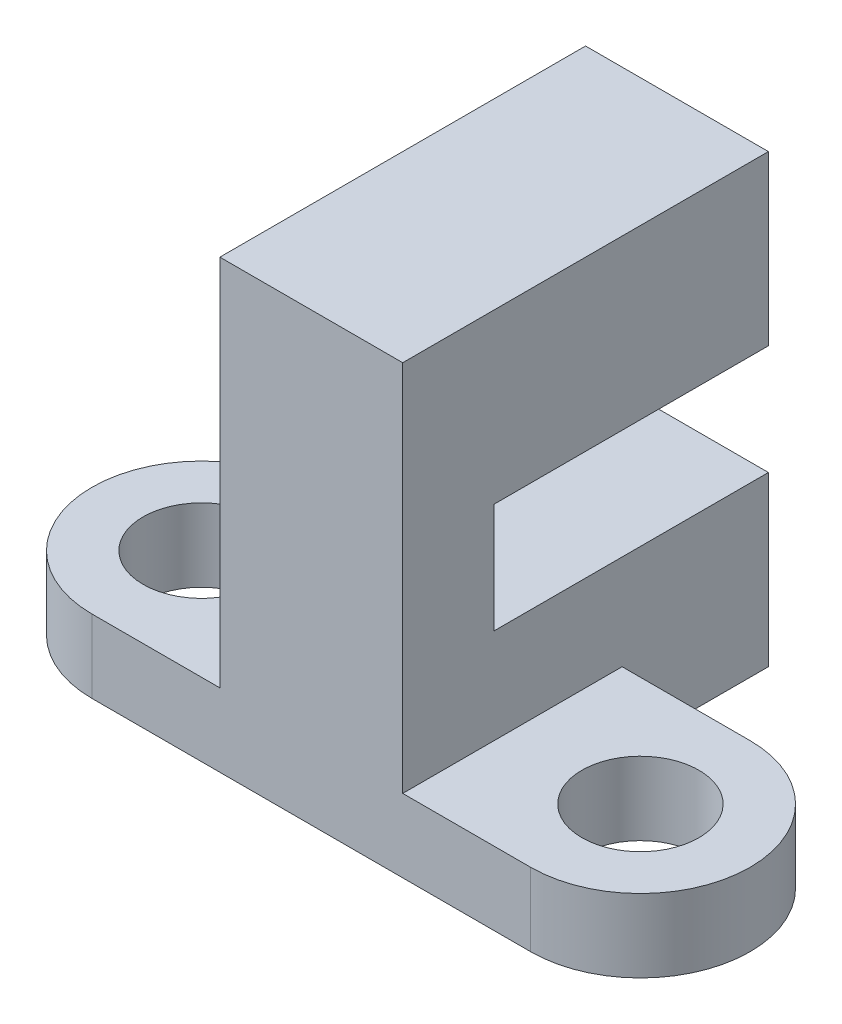
SolidWorks part; units mm, degrees
material "ABS"
ref_plane "Front" through (0, 0, 0) normal (0, 0, 1) x (1, 0, 0)
ref_plane "Top" through (0, 0, 0) normal (0, 1, 0) x (1, 0, 0)
ref_plane "Right" through (0, 0, 0) normal (1, 0, 0) x (0, 0, -1)
sketch "Эскиз1" plane through (0, 0, 0) normal (0, 1, 0) x (1, 0, 0)
  line L0 (-6, 3) -> (6, 3)
  line L1 (-6, -3) -> (6, -3)
  arc A0 (-6, -3) -> (-6, 3) centre (-6, 0) cw
  arc A1 (6, 3) -> (6, -3) centre (6, 0) cw
  circle A2 centre (-6, 0) radius 1.6
  circle A3 centre (6, 0) radius 1.6
  point P4 (0, 3)
  point P5 (0, -3)
  dimension "D3" = 3.2
  dimension "D1" = 6
  dimension "D2" = 12
extrude "База" add sketch "Эскиз1" along normal blind 2
sketch "Эскиз2" plane through (0, 0, 0) normal (0, -1, 0) x (1, 0, 0)
  line L0 (-6, 3) -> (6, 3) construction
  line L1 (-2.5, 3) -> (2.5, 3)
  line L2 (-2.5, 3) -> (-2.5, -7)
  line L3 (-2.5, -7) -> (2.5, -7)
  line L4 (2.5, 3) -> (2.5, -7)
  point P7 (0, 3)
  dimension "D1" = 5
  dimension "D2" = 10
extrude "Датчик" add sketch "Эскиз2" against normal blind 12.2
sketch "Эскиз3" plane through (0, 0, -7) normal (0, 0, -1) x (-1, 0, 0)
  line L0 (-2.5, 12.2) -> (-2.5, 0) construction
  line L1 (-2.5, 7.6) -> (2.5, 7.6)
  line L2 (-2.5, 7.6) -> (-2.5, 4.6)
  line L3 (-2.5, 4.6) -> (2.5, 4.6)
  line L4 (2.5, 7.6) -> (2.5, 4.6)
  line L5 (2.5, 12.2) -> (2.5, 0) construction
  line L6 (0, 7.6) -> (0, 12.2) construction
  line L7 (2.5, 12.2) -> (-2.5, 12.2) construction
  line L8 (0, 4.6) -> (0, 0) construction
  dimension "D1" = 3
extrude "Вырез датчика" cut sketch "Эскиз3" against normal blind 7.5
